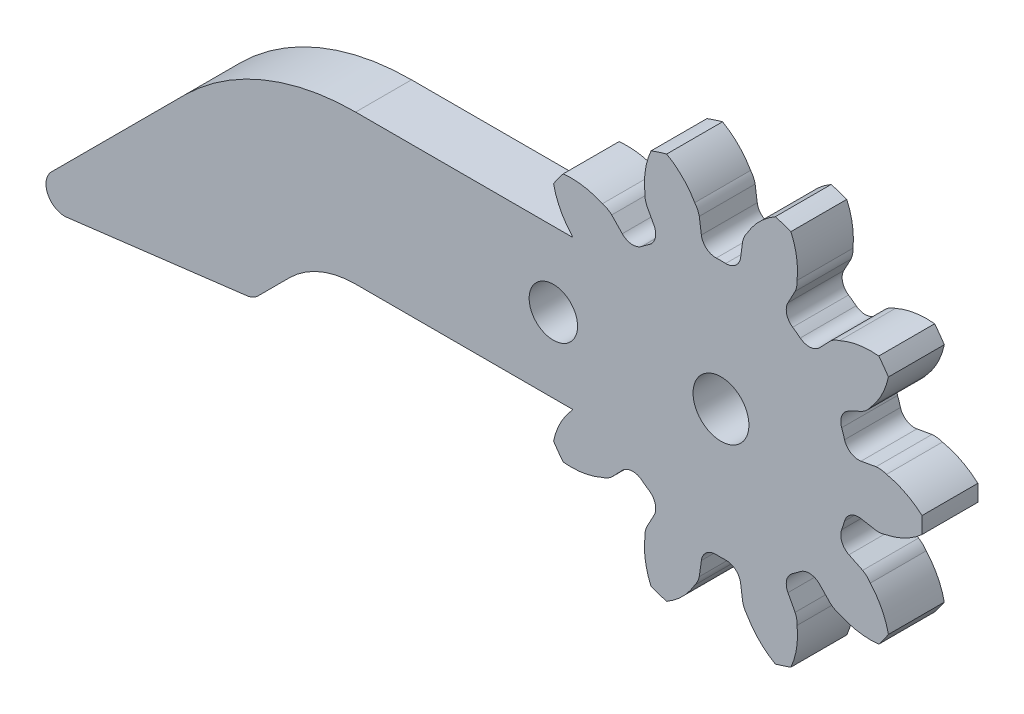
SolidWorks part; units mm, degrees
material "Acrílico (médio-alto impacto)"
ref_plane "Plano frontal" through (0, 0, 0) normal (0, 0, 1) x (1, 0, 0)
ref_plane "Plano superior" through (0, 0, 0) normal (0, 1, 0) x (1, 0, 0)
ref_plane "Plano direito" through (0, 0, 0) normal (1, 0, 0) x (0, 0, -1)
sketch "Posicionamentos" plane through (0, 0, 0) normal (0, 0, 1) x (1, 0, 0)
  circle A0 centre (0, 0) radius 10.8
  circle A1 centre (0, 0) radius 9
  circle A2 centre (0, 0) radius 6.8994
  circle A3 centre (0, 0) radius 8.4572
  dimension "De" = 21.6
  dimension "DP" = 18
  dimension "DI" = 13.7988
  dimension "DB" = 16.9145
sketch "Dente" plane through (0, 0, 0) normal (0, 0, 1) x (1, 0, 0)
  line L0 (0, 0) -> (0, 10.8) construction
  line L1 (0, 0) -> (-3.3374, 10.2714) construction
  line L2 (-1.1653, 8.3766) -> (-0.9506, 6.8336)
  line L3 (-1.4079, 8.8892) -> (0, 0) construction
  line L4 (-3.9809, 7.4617) -> (-3.2476, 6.0873)
  circle A0 centre (0, 0) radius 10.8 construction
  arc A1 (-2.9146, 10.3993) -> (-1.4079, 8.8892) centre (-4.9667, 6.8452) cw
  circle A2 centre (0, 0) radius 9 construction
  arc A3 (-1.4079, 8.8892) -> (-1.1653, 8.3766) centre (-2.3795, 8.1156) cw
  circle A4 centre (0, 0) radius 8.4572 construction
  circle A5 centre (0, 0) radius 6.8994 construction
  arc A6 (-4.0859, 8.0191) -> (-3.9809, 7.4617) centre (-2.8451, 7.9643) ccw
  arc A7 (-3.7546, 10.1263) -> (-4.0859, 8.0191) centre (-0.0054, 8.4572) ccw
  arc A8 (-3.2476, 6.0873) -> (-0.9506, 6.8336) centre (0, 0) cw
  arc A9 (-3.7546, 10.1263) -> (-2.9146, 10.3993) centre (0, 0) cw
  arc A10 (-4.0859, 8.0191) -> (-1.4079, 8.8892) centre (0, 0) cw construction
  dimension "R" = 4.104
  dimension "R1" = 1.242
  dimension "alpha" = 9
  dimension "Aposicionador" = 18
  dimension "D1" = 2.8274
sketch "Braço" plane through (0, 0, 0) normal (0, 0, 1) x (1, 0, 0)
  line L0 (0, 0) -> (-25, 0) construction
  line L1 (0, 4) -> (-25, 4)
  line L2 (-25, 4) -> (-38, -9)
  line L3 (-38, -9) -> (-25.1027, -7.4164)
  line L4 (-25.1027, -7.4164) -> (-21.6863, -4)
  line L5 (-21.6863, -4) -> (0, -4)
  line L6 (0, -4) -> (0, 4)
  line L7 (-38, -9) -> (-22.7813, -9) construction
  line L8 (-29.0514, -0.0514) -> (-23.3945, -5.7082) construction
  circle A0 centre (0, 0) radius 9 construction
  circle A1 centre (0, 0) radius 9 construction
  point P9 (-9, 0)
  dimension "D5" = 18
  dimension "D1" = 38
  dimension "D2" = 7
  dimension "D3" = 135
  dimension "D4" = 8
extrude "Base" add sketch "Posicionamentos" along normal blind 3 contours A2
extrude "Base Dente" add sketch "Dente" along normal through all
fillet "Raio Dente" radius 0.7789 2 edges at (-3.2476, 6.0873, 1.5) (-0.9506, 6.8336, 1.5)
pattern_circular "PadrãoCircular1" count 10 over 360 about axis through (0, 0, 0) along (0, 0, 1) skipping 8 of "Base Dente", "Raio Dente"
extrude "Ressalto-extrusão3" add sketch "Braço" along normal through all contours L5 L6 L1 L2 L3 L4
hole_wizard "Furo de diâmetro Ø3.0 (3)1" positions "Esboço4" profile "Esboço5" hole size "Ø3.0" standard "ISO" end condition through all
sketch "Esboço4" plane through (0, 0, 3) normal (0, 0, 1) x (1, 0, 0)
  point P0 (0, 0)
sketch "Esboço5" plane through (0, 0, 3) normal (1, 0, 0) x (0, -1, 0)
  line L0 (0, 0) -> (0, 3)
  line L1 (0, 3) -> (1.5, 3)
  line L2 (1.5, 3) -> (1.5, 0)
  line L5 (1.5, 0) -> (0, 0)
  line L11 (0, -6.35) -> (0, 107.95) construction
  dimension "Thru Hole Dia." = 3
  dimension "Thru Hole Depth" = 3
hole_wizard "Furo de diâmetro Ø2.6 (2.6)1" positions "Esboço6" profile "Esboço7" hole size "Ø2.6" standard "ISO" end condition through all
sketch "Esboço6" plane through (0, 0, 3) normal (0, 0, 1) x (1, 0, 0)
  point P0 (-9, 0)
sketch "Esboço7" plane through (-9, 0, 3) normal (1, 0, 0) x (0, -1, 0)
  line L0 (0, 0) -> (0, 3)
  line L1 (0, 3) -> (1.3, 3)
  line L2 (1.3, 3) -> (1.3, 0)
  line L5 (1.3, 0) -> (0, 0)
  line L11 (0, -6.35) -> (0, 107.95) construction
  dimension "Thru Hole Dia." = 2.6
  dimension "Thru Hole Depth" = 3
fillet "Filete2" radius 5 1 edges at (-21.6863, -4, 1.5)
fillet "Filete3" radius 13 1 edges at (-25, 4, 1.5)
fillet "Filete4" radius 1 2 edges at (-38, -9, 1.5) (-25.1027, -7.4164, 1.5)
equation "\"Z\"= \"Z@Padrão\""
equation "\"M\"= \"DP\" / \"Z\"'Módulo"
equation "\"DP\"= \"DP@Padrão\""
equation "\"P\"= \"M\" * pi'Passo"
equation "\"S\"= \"P\" / 2'Espessura Circular"
equation "\"V\"= \"S\"'Vão"
equation "\"sc\"= 1"
equation "\"de\"= \"M\" * ( \"Z\" + 2 )'Diâmetro Externo"
equation "\"di\"= \"M\" * ( \"Z\" - 2.334 )'Diâmetro Interno"
equation "\"Phi\"= 20'ângulo de pressão"
equation "\"db\"= \"DP\" * cos ( \"Phi\" )'Diâmetro do círculo de base"
equation "\"a\"= \"M\"'Altura da cabeça do dente"
equation "\"b\"= 1.167 * \"M\"'Altura do pé do dente"
equation "\"h\"= \"a\" + \"b\"'Altura do dente"
equation "\"e\"= .167 * \"M\"'Folga no pé do dente"
equation "\"alpha\"= 90 / \"Z\"'ângulo do dente"
equation "\"f\"= \"ValorF@Padrão\""
equation "\"f1\"= \"ValorF1@Padrão\""
equation "\"r\"= \"f\" * \"M\" 'Raio do dente"
equation "\"r1\"= \"f1\" * \"M\"'Rario 1 do dente"
equation "\"De@Posicionamentos\" = \"de\""
equation "\"DP@Posicionamentos\" = \"DP\""
equation "\"DI@Posicionamentos\" = \"di\""
equation "\"DB@Posicionamentos\" = \"db\""
equation "\"R@Dente\" = \"r\""
equation "\"R1@Dente\" = \"r1\""
equation "\"alpha@Dente\" = \"alpha\""
equation "\"D1@PadrãoCircular1\"=\"Z\""
equation "\"rd\"= ( \"db\" - \"di\" ) / 4"
equation "\"D1@Raio Dente\"=\"rd\""
equation "\"Posicionador\"= 1"
equation "\"Aposicionador\"= IIF ( \"Posicionador\" = 0 , 0 , ( \"alpha\" * 2 ) )"
equation "\"Aposicionador@Dente\"=\"Aposicionador\""
equation "\"D1@Dente\"=\"S\""
